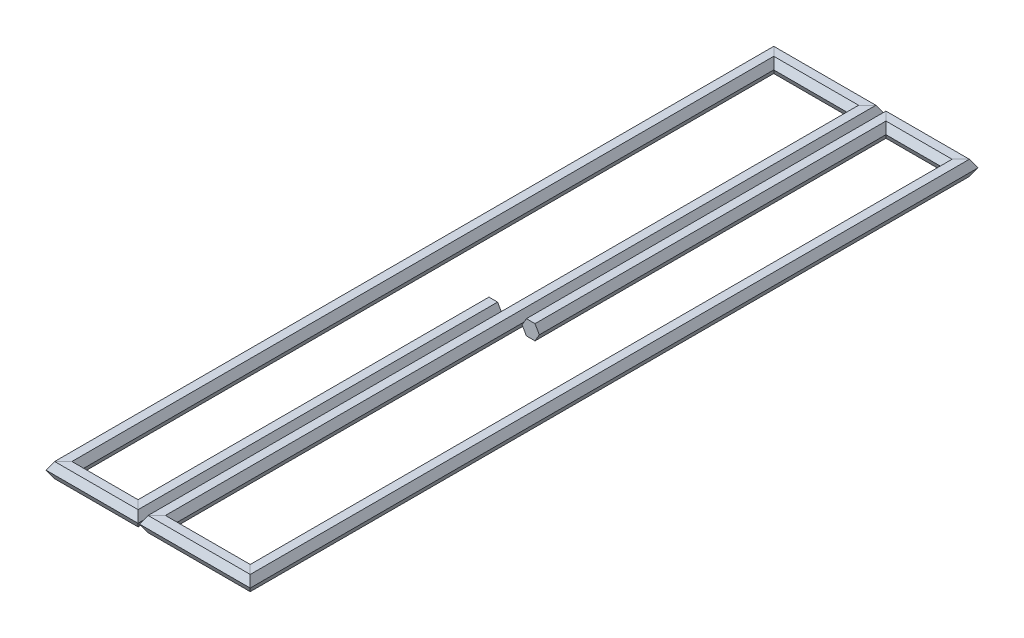
SolidWorks part; units mm, degrees
ref_plane "Front Plane" through (0, 0, 0) normal (0, 0, 1) x (1, 0, 0)
ref_plane "Top Plane" through (0, 0, 0) normal (0, 1, 0) x (1, 0, 0)
ref_plane "Right Plane" through (0, 0, 0) normal (1, 0, 0) x (0, 0, -1)
sketch "Sketch2" plane through (0, 0, 0) normal (0, 1, 0) x (1, 0, 0)
  line L0 (-25, 0) -> (-25, -475)
  line L1 (-150, -500) -> (150, -500) construction
  line L2 (-150, -500) -> (-150, 500) construction
  line L3 (-150, 500) -> (150, 500) construction
  line L4 (150, -500) -> (150, 500) construction
  line L5 (-150, -500) -> (150, 500) construction
  line L6 (-150, 500) -> (150, -500) construction
  line L7 (-25, -475) -> (-125, -475)
  line L8 (-125, -475) -> (-125, 475)
  line L9 (-125, 475) -> (0, 475)
  line L10 (0, 475) -> (0, -475)
  line L11 (0, -475) -> (125, -475)
  line L12 (125, -475) -> (125, 475)
  line L13 (125, 475) -> (25, 475)
  line L14 (25, 475) -> (25, 0)
  line L15 (-125, -475) -> (-125, -500) construction
  line L17 (150, 475) -> (125, 475) construction
  line L18 (-125, 475) -> (-125, 500) construction
  line L19 (-125, 475) -> (-150, 475) construction
  line L20 (-25, 0) -> (0, 0) construction
  line L21 (0, 0) -> (25, 0) construction
  line L22 (-12.5, 0) -> (12.5, 0)
  point P0 (0, 0)
  point P25 (-12.5, 0)
  point P27 (12.5, 0)
  point P30 (0, 0)
  dimension "D1" = 300
  dimension "D2" = 1000
  dimension "Half_width" = 25
sketch "Sketch3" plane through (0, 0, 0) normal (0, 0, 1) x (1, 0, 0)
  line L1 (36.547, 0) -> (30.7735, 10)
  line L2 (30.7735, 10) -> (19.2265, 10)
  line L3 (19.2265, 10) -> (13.453, 0)
  line L4 (13.453, 0) -> (19.2265, -10)
  line L5 (19.2265, -10) -> (30.7735, -10)
  line L6 (30.7735, -10) -> (36.547, 0)
  circle A0 centre (25, 0) radius 10 construction
  dimension "D1" = 20
sweep "Sweep2" add profiles "Sketch3" path "Sketch2"
sketch "Sketch4" plane through (0, 0, 0) normal (0, 0, 1) x (1, 0, 0)
